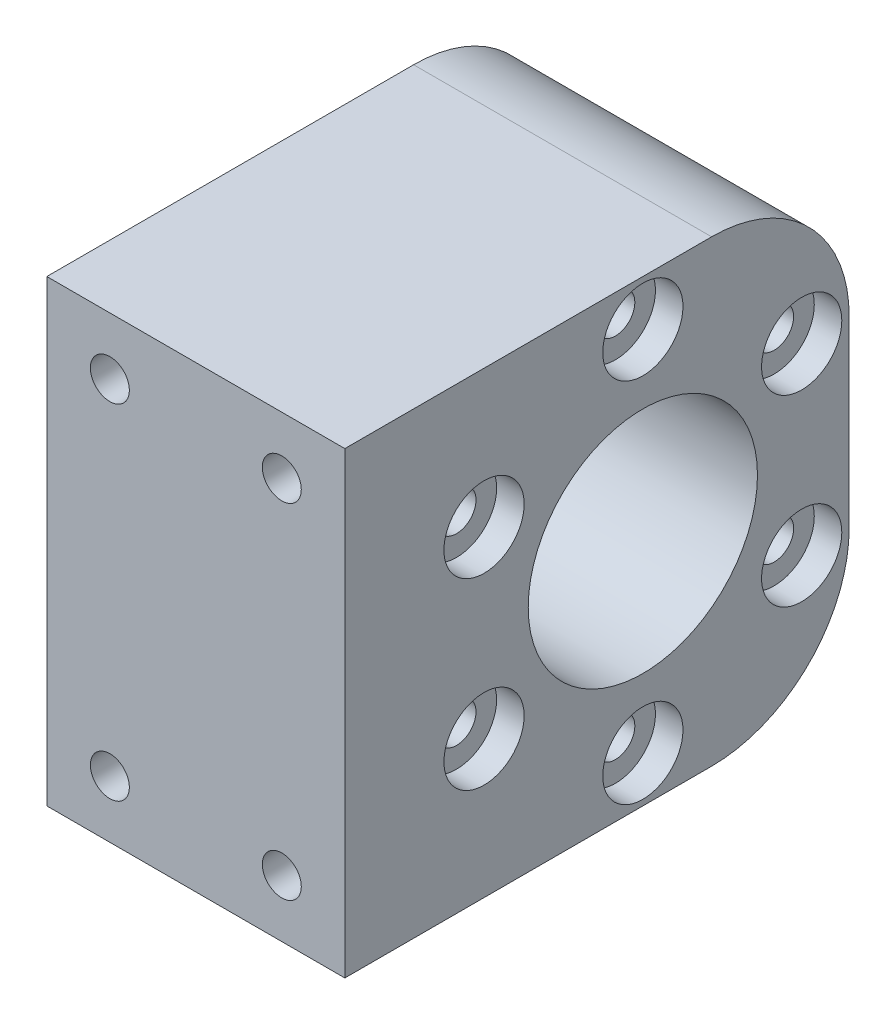
SolidWorks part; units mm, degrees
material "6063-T5"
ref_plane "Front" through (0, 0, 0) normal (0, 0, 1) x (1, 0, 0)
ref_plane "Top" through (0, 0, 0) normal (0, 1, 0) x (1, 0, 0)
ref_plane "Right" through (0, 0, 0) normal (1, 0, 0) x (0, 0, -1)
sketch "Croquis1" plane through (0, 0, 0) normal (0, 0, 1) x (1, 0, 0)
  line L1 (-13, -20) -> (13, -20)
  line L2 (-13, -20) -> (-13, 20)
  line L3 (-13, 20) -> (13, 20)
  line L4 (13, -20) -> (13, 20)
  line L5 (-13, -20) -> (13, 20) construction
  line L6 (-13, 20) -> (13, -20) construction
  point P0 (0, 0)
  dimension "D1" = 40
  dimension "D2" = 26
extrude "Saliente-Extruir1" add sketch "Croquis1" along normal mid plane 52
hole_wizard "Taladro de margen para M31" positions "Croquis2" profile "Croquis3" hole size "M3" standard "Ansi Metric"
sketch "Croquis2" plane through (0, 0, 26) normal (0, 0, 1) x (1, 0, 0)
  line L1 (7.5, -15) -> (-7.5, -15) construction
  line L2 (7.5, -15) -> (7.5, 15) construction
  line L3 (7.5, 15) -> (-7.5, 15) construction
  line L4 (-7.5, -15) -> (-7.5, 15) construction
  line L5 (7.5, -15) -> (-7.5, 15) construction
  line L6 (7.5, 15) -> (-7.5, -15) construction
  point P2 (-7.5, 15)
  point P47 (7.5, -15)
  point P48 (7.5, 15)
  point P49 (-7.5, -15)
  dimension "D1" = 30
  dimension "D2" = 15
sketch "Croquis3" plane through (-7.5, 15, 26) normal (1, 0, 0) x (0, -1, 0)
  line L0 (0, 0) -> (0, 16.0215)
  line L1 (0, 16.0215) -> (1.7, 15)
  line L2 (1.7, 15) -> (1.7, 0)
  line L5 (1.7, 0) -> (0, 0)
  line L10 (0, 16.0215) -> (-1.7, 15) construction
  line L11 (0, -6.35) -> (0, 107.95) construction
  dimension "Diámetro de taladro" = 3.4
  dimension "Profundidad de taladro" = 15
  dimension "Ángulo de perforador" = 118
hole_wizard "Refrentado para tornillo con cabeza troncocónica de M31" positions "Croquis4" profile "Croquis6" counterbore size "M3" standard "Ansi Metric" end condition through all
sketch "Croquis4" plane through (13, 0, 0) normal (1, 0, 0) x (0, 0, -1)
  line L0 (0, 14.3) -> (0, -14.3) construction
  point P1 (0, 16)
  point P11 (13.8564, 8)
  point P12 (13.8564, -8)
  point P13 (0, -16)
  point P14 (-13.8564, -8)
  point P15 (-13.8564, 8)
  dimension "D1" = 16
  dimension "D2" = 6
sketch "Croquis6" plane through (13, 16, 0) normal (0, 1, 0) x (0, 0, -1)
  line L0 (0, 0) -> (0, 26)
  line L1 (0, 26) -> (1.7, 26)
  line L3 (1.7, 26) -> (1.7, 2.4)
  line L4 (1.7, 2.4) -> (3.5, 2.4)
  line L5 (3.5, 2.4) -> (3.5, 0)
  line L7 (3.5, 0) -> (0, 0)
  line L11 (0, -6.35) -> (0, 107.95) construction
  dimension "Diámetro de taladro hasta el siguiente" = 3.4
  dimension "Profundidad de taladro hasta el siguiente" = 26
  dimension "Diámetro de refrentado" = 7
  dimension "Profundidad de refrentado" = 2.4
sketch "Croquis7" plane through (-13, 0, 0) normal (-1, 0, 0) x (0, 0, 1)
  circle A0 centre (0, 0) radius 10
  dimension "D1" = 20
extrude "Cortar-Extruir1" cut sketch "Croquis7" against normal through all
sketch "Croquis9" plane through (13, 0, 0) normal (1, 0, 0) x (0, 0, -1)
  line L0 (-26, -20) -> (26, -20) construction
  line L1 (26, 20) -> (18, 20)
  line L2 (26, 20) -> (26, -20)
  line L3 (26, -20) -> (18, -20)
  line L4 (18, 20) -> (18, -20)
  dimension "D1" = 8
extrude "Cortar-Extruir3" cut sketch "Croquis9" against normal through all
fillet "Redondeo3" radius 12 2 edges at (0, -20, -18) (0, 20, -18)
